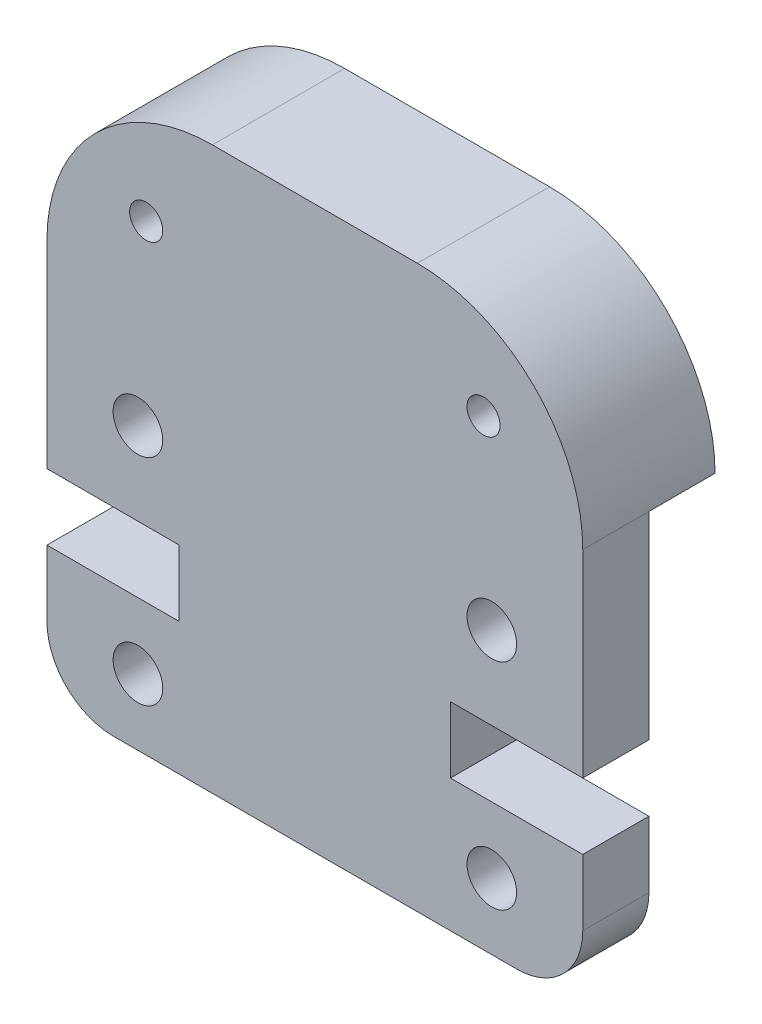
SolidWorks part; units mm, degrees
ref_plane "Front Plane" through (0, 0, 0) normal (0, 0, 1) x (1, 0, 0)
ref_plane "Top Plane" through (0, 0, 0) normal (0, 1, 0) x (1, 0, 0)
ref_plane "Right Plane" through (0, 0, 0) normal (1, 0, 0) x (0, 0, -1)
sketch "Sketch1" plane through (0, 0, 0) normal (0, 0, 1) x (1, 0, 0)
  line L0 (0, 16.98) -> (0, 0) construction
  line L1 (3.1, 16.98) -> (-3.1, 16.98)
  line L2 (6.1, 0) -> (-6.1, 0)
  line L3 (-8.1, 6) -> (-4.1, 6)
  line L4 (-4.1, 6) -> (-4.1, 4)
  line L5 (-4.1, 4) -> (-8.1, 4)
  line L6 (-8.1, 2) -> (-8.1, 4)
  line L7 (8.1, 11.98) -> (8.1, 6)
  line L8 (-8.1, 11.98) -> (-8.1, 6)
  line L24 (8.1, 2) -> (8.1, 4)
  line L27 (4.1, 4) -> (8.1, 4)
  line L30 (4.1, 6) -> (4.1, 4)
  line L31 (8.1, 6) -> (4.1, 6)
  circle A0 centre (-5.35, 2) radius 0.75
  circle A1 centre (-5.1, 13.98) radius 0.5
  arc A2 (-8.1, 11.98) -> (-3.1, 16.98) centre (-3.1, 11.98) cw
  arc A3 (-6.1, 0) -> (-8.1, 2) centre (-6.1, 2) cw
  circle A4 centre (-5.35, 8.5) radius 0.75
  circle A10 centre (5.35, 8.5) radius 0.75
  arc A12 (6.1, 0) -> (8.1, 2) centre (6.1, 2) ccw
  arc A14 (8.1, 11.98) -> (3.1, 16.98) centre (3.1, 11.98) ccw
  circle A16 centre (5.1, 13.98) radius 0.5
  circle A18 centre (5.35, 2) radius 0.75
  dimension "D1" = 1.5
  dimension "D2" = 1
  dimension "D3" = 16.98
  dimension "D4" = 2
  dimension "D5" = 5
  dimension "D6" = 6.1
  dimension "D7" = 3
  dimension "D8" = 3
  dimension "D9" = 2.75
  dimension "D10" = 8.5
extrude "Boss-Extrude1" add sketch "Sketch1" along normal blind 4
sketch "Sketch2" plane through (0, 0, 0) normal (0, 0, 1) x (1, 0, 0)
  line L0 (-8.1, 0) -> (8.1, 0)
  line L1 (8.1, 0) -> (8.1, 11.98)
  line L2 (8.1, 11.98) -> (-8.1, 11.98)
  line L3 (-8.1, 11.98) -> (-8.1, 0)
extrude "Cut-Extrude1" cut sketch "Sketch2" along normal blind 2
equation "\"D6@Sketch1\"= ( \"fingerWidth@parametersSketch@prostheticParameters.SLDPRT\" - 4 ) / 2'Finger Width - Radius"
equation "\"D3@Sketch1\"= ( \"HL@parametersSketch@prostheticParameters.SLDPRT\" * 0.108 ) - 3 'DIP Legth-Sil. Sh. DIP"
